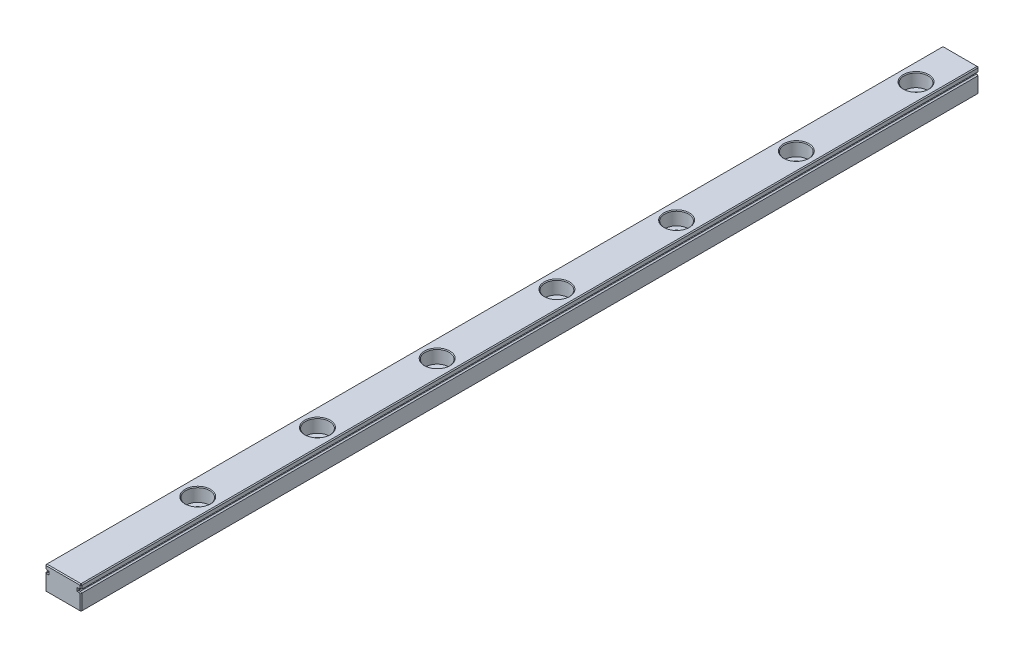
SolidWorks part; units mm, degrees
material "AISI 304"
ref_plane "Front Plane" through (0, 0, 0) normal (0, 0, 1) x (1, 0, 0)
ref_plane "Top Plane" through (0, 0, 0) normal (0, 1, 0) x (1, 0, 0)
ref_plane "Right Plane" through (0, 0, 0) normal (1, 0, 0) x (0, 0, -1)
sketch "Sketch1" plane through (0, 0, 0) normal (0, 0, 1) x (1, 0, 0)
  line L0 (0, 0) -> (0, 8) construction
  line L1 (0, 8) -> (12, 8)
  line L2 (0, 0) -> (12, 0)
  line L3 (0, 8) -> (0, 6.75)
  line L4 (0, 6.75) -> (0.5, 6.25) construction
  line L5 (0.5, 6.25) -> (1, 6.25)
  line L6 (0.5, 5.75) -> (0, 5.25) construction
  line L7 (0, 5.25) -> (0, 0)
  line L8 (1, 6.25) -> (1, 5.75)
  line L9 (1, 5.75) -> (0.5, 5.75)
  line L10 (0.5, 5.75) -> (0.75, 6) construction
  line L11 (0.75, 6) -> (0.5, 6.25) construction
  line L12 (0, 6.75) -> (0, 6.559)
  line L13 (0, 5.25) -> (0, 5.441)
  line L14 (6, 8) -> (6, 0) construction
  line L15 (11.25, 6) -> (11.5, 6.25) construction
  line L16 (11.5, 5.75) -> (11.25, 6) construction
  line L17 (11.5, 5.75) -> (12, 5.25) construction
  line L18 (12, 6.75) -> (11.5, 6.25) construction
  line L19 (12, 0) -> (12, 8) construction
  line L20 (12, 5.25) -> (12, 5.441)
  line L21 (12, 6.75) -> (12, 6.559)
  line L22 (11, 5.75) -> (11.5, 5.75)
  line L23 (11, 6.25) -> (11, 5.75)
  line L24 (12, 5.25) -> (12, 0)
  line L25 (11.5, 6.25) -> (11, 6.25)
  line L26 (12, 8) -> (12, 6.75)
  arc A0 (0, 5.441) -> (0.5, 5.75) centre (0, 6) ccw
  arc A1 (0.5, 6.25) -> (0, 6.559) centre (0, 6) ccw
  arc A2 (11.5, 6.25) -> (12, 6.559) centre (12, 6) cw
  arc A3 (12, 5.441) -> (11.5, 5.75) centre (12, 6) cw
  point P4 (1, 6)
  point P28 (11, 6)
  dimension "D1" = 8
  dimension "D2" = 6
  dimension "D3" = 0.5
  dimension "D4" = 45
  dimension "D5" = 2
  dimension "D6" = 1
extrude "Boss-Extrude1" add sketch "Sketch1" along normal blind 300
chamfer "Chamfer1" distance 0.3 angle 45 36 edges at (0, 0, 150) (12, 0, 150) (0, 8, 150) (12, 8, 150) (0.2939, 5.5245, 300) (0.75, 5.75, 300) (1, 6, 300) (0.75, 6.25, 300) (0.2939, 6.4755, 300) (0, 7.2795, 300) (6, 8, 300) (12, 7.2795, 300) (11.7061, 6.4755, 300) (11.25, 6.25, 300) (11, 6, 300) (11.25, 5.75, 300) (11.7061, 5.5245, 300) (12, 2.7205, 300) (6, 0, 300) (0, 2.7205, 300) (12, 2.7205, 0) (11.7061, 5.5245, 0) (11.25, 5.75, 0) (11, 6, 0) (11.25, 6.25, 0) (11.7061, 6.4755, 0) (12, 7.2795, 0) (6, 0, 0) (0, 2.7205, 0) (0.2939, 5.5245, 0) (0.75, 5.75, 0) (1, 6, 0) (0.75, 6.25, 0) (0.2939, 6.4755, 0) (0, 7.2795, 0) (6, 8, 0)
hole_wizard "CBORE for M5 Hex Head Bolt1" positions "3DSketch1" profile "Sketch3" counterbore size "M5" standard "ANSI Metric" end condition through all
sketch3d "3DSketch1"
  line L0 (6, 8, 0) -> (6, 8, 15) construction
  line L1 (11.7, 8, 0) -> (0.3, 8, 0) construction
  point P0 (6, 8, 15)
  dimension "D1" = 15
sketch "Sketch3" plane through (6, 8, 15) normal (1, 0, 0) x (0, 0, 1)
  line L0 (0, 0) -> (0, 8)
  line L1 (2.25, 7.75) -> (2.5, 8)
  line L2 (4, 4.5) -> (2.25, 4.5)
  line L3 (2.25, 4.5) -> (2.25, 7.75)
  line L5 (4, 4.5) -> (4, 0.25)
  line L6 (4, 0.25) -> (4.25, 0)
  line L7 (4.25, 0) -> (0, 0)
  line L8 (-4, 0.25) -> (-4.25, 0) construction
  line L11 (0, -6.35) -> (0, 107.95) construction
  line L12 (2.5, 8) -> (0, 8)
  line L13 (-2.25, 7.75) -> (-2.5, 8) construction
  dimension "Thru Hole Dia." = 4.5
  dimension "Thru Hole Depth" = 8
  dimension "C'Bore Dia." = 8
  dimension "C'Bore Depth" = 4.5
  dimension "Near C'Sink Dia." = 8.5
  dimension "Near C'Sink Angle" = 90
  dimension "Far C'Sink Dia." = 5
  dimension "Far C'Sink Angle" = 90
pattern_linear "LPattern1" count 7 spacing 40 along (0, 0, 1) of "CBORE for M5 Hex Head Bolt1"
